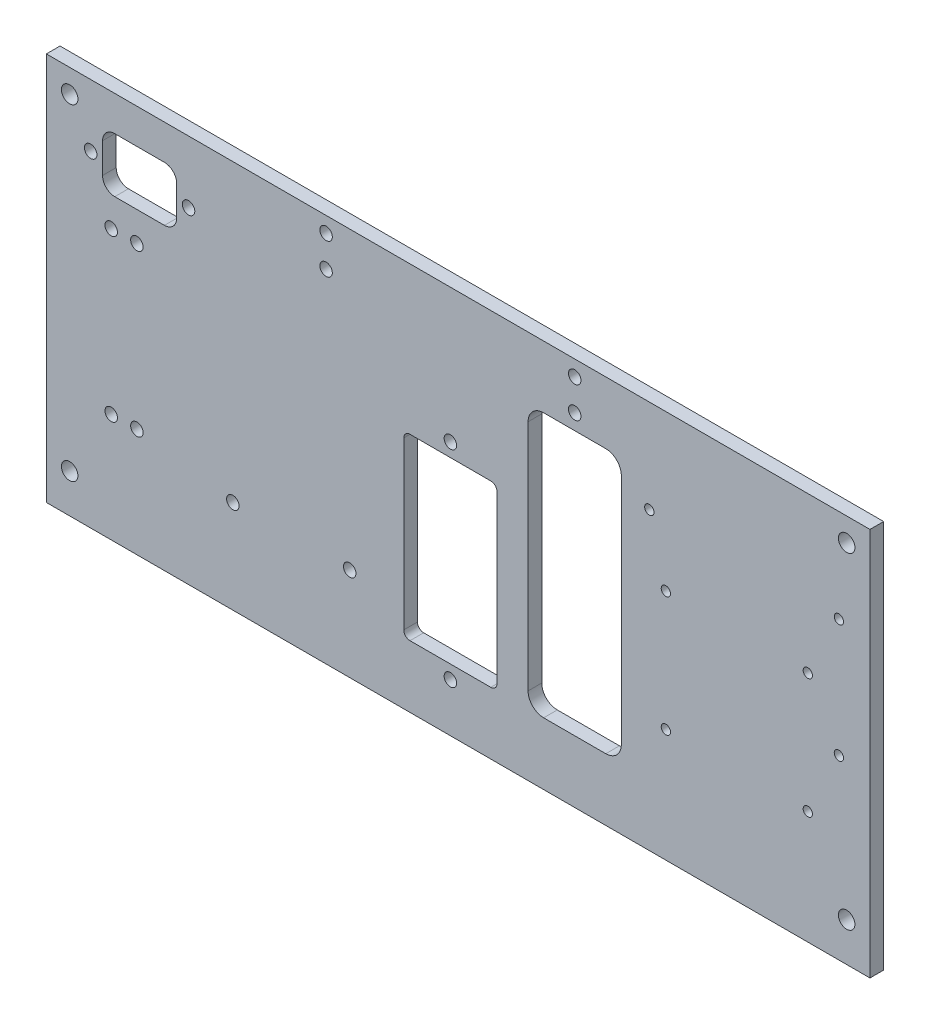
SolidWorks part; units mm, degrees
material "Acrylic (Medium-high impact)"
ref_plane "Front Plane" through (0, 0, 0) normal (0, 0, 1) x (1, 0, 0)
ref_plane "Top Plane" through (0, 0, 0) normal (0, 1, 0) x (1, 0, 0)
ref_plane "Right Plane" through (0, 0, 0) normal (1, 0, 0) x (0, 0, -1)
sketch "Sketch1" plane through (0, 0, 0) normal (0, 0, 1) x (1, 0, 0)
  line L1 (-168.275, 79.375) -> (168.275, 79.375)
  line L2 (-168.275, 79.375) -> (-168.275, -79.375)
  line L3 (-168.275, -79.375) -> (168.275, -79.375)
  line L4 (168.275, 79.375) -> (168.275, -79.375)
  line L5 (-168.275, 79.375) -> (168.275, -79.375) construction
  line L6 (-168.275, -79.375) -> (168.275, 79.375) construction
  point P0 (0, 0)
  dimension "D1" = 158.75
  dimension "D2" = 336.55
extrude "Boss-Extrude1" add sketch "Sketch1" along normal blind 5.588 contours L1 L4 L3 L2
hole_wizard "1/4 Clearance Hole1" positions "Sketch3" profile "Sketch2" hole size "1/4" standard "ANSI Inch" end condition up to next
sketch "Sketch3" plane through (0, 0, 0) normal (0, 0, -1) x (-1, 0, 0)
  line L1 (-158.75, 69.85) -> (158.75, 69.85) construction
  line L2 (-158.75, 69.85) -> (-158.75, -63.5) construction
  line L3 (-158.75, -63.5) -> (158.75, -63.5) construction
  line L4 (158.75, 69.85) -> (158.75, -63.5) construction
  line L5 (168.275, 79.375) -> (-168.275, 79.375) construction
  line L6 (-168.275, 79.375) -> (-168.275, -79.375) construction
  line L10 (168.275, 79.375) -> (168.275, -79.375) construction
  line L11 (168.275, -79.375) -> (-168.275, -79.375) construction
  point P1 (-158.75, 69.85)
  point P2 (158.75, -63.5)
  point P283 (-158.75, -63.5)
  point P284 (158.75, 69.85)
  dimension "D1" = 9.525
  dimension "D2" = 9.525
  dimension "D3" = 9.525
  dimension "D4" = 15.875
sketch "Sketch2" plane through (158.75, 69.85, 0) normal (1, 0, 0) x (0, 1, 0)
  line L0 (0, 0) -> (0, 5.588)
  line L1 (0, 5.588) -> (3.3782, 5.588)
  line L2 (3.3782, 5.588) -> (3.3782, 0)
  line L5 (3.3782, 0) -> (0, 0)
  line L11 (0, -6.35) -> (0, 107.95) construction
  dimension "Thru Hole Dia." = 6.7564
  dimension "Thru Hole Depth" = 5.588
hole_wizard "#6 Clearance Hole1" positions "Sketch6" profile "Sketch7" hole size "#6" standard "ANSI Inch" end condition up to next
sketch "Sketch6" plane through (0, 0, 0) normal (0, 0, -1) x (-1, 0, 0)
  line L1 (-155.575, 41.275) -> (-78.105, 41.275) construction
  line L2 (-155.575, 41.275) -> (-155.575, -6.985) construction
  line L3 (-155.575, -6.985) -> (-78.105, -6.985) construction
  line L4 (-78.105, 41.275) -> (-78.105, -6.985) construction
  line L5 (-168.275, 79.375) -> (-168.275, -79.375) construction
  line L6 (168.275, 79.375) -> (-168.275, 79.375) construction
  point P0 (-155.575, 41.275)
  point P105 (-155.575, -6.985)
  point P106 (-78.105, 41.275)
  dimension "D1" = 77.47
  dimension "D2" = 48.26
  dimension "D3" = 12.7
  dimension "D4" = 38.1
sketch "Sketch7" plane through (155.575, 41.275, 0) normal (1, 0, 0) x (0, 1, 0)
  line L0 (0, 0) -> (0, 5.588)
  line L1 (0, 5.588) -> (1.8986, 5.588)
  line L2 (1.8986, 5.588) -> (1.8986, 0)
  line L5 (1.8986, 0) -> (0, 0)
  line L11 (0, -6.35) -> (0, 107.95) construction
  dimension "Thru Hole Dia." = 3.7973
  dimension "Thru Hole Depth" = 5.588
hole_wizard "#6 Clearance Hole2" positions "Sketch9" profile "Sketch10" hole size "#6" standard "ANSI Inch" end condition up to next
sketch "Sketch9" plane through (0, 0, 0) normal (0, 0, -1) x (-1, 0, 0)
  line L1 (-142.875, 15.875) -> (-84.875, 15.875) construction
  line L2 (-142.875, 15.875) -> (-142.875, -33.125) construction
  line L3 (-142.875, -33.125) -> (-84.875, -33.125) construction
  line L4 (-84.875, 15.875) -> (-84.875, -33.125) construction
  line L5 (-168.275, 79.375) -> (-168.275, -79.375) construction
  line L6 (168.275, 79.375) -> (-168.275, 79.375) construction
  point P0 (-142.875, 15.875)
  point P1 (-84.875, -33.125)
  point P148 (-142.875, -33.125)
  point P149 (-84.875, 15.875)
  dimension "D1" = 58
  dimension "D2" = 49
  dimension "D3" = 25.4
  dimension "D4" = 63.5
sketch "Sketch10" plane through (142.875, 15.875, 0) normal (1, 0, 0) x (0, 1, 0)
  line L0 (0, 0) -> (0, 5.588)
  line L1 (0, 5.588) -> (1.8986, 5.588)
  line L2 (1.8986, 5.588) -> (1.8986, 0)
  line L5 (1.8986, 0) -> (0, 0)
  line L11 (0, -6.35) -> (0, 107.95) construction
  dimension "Thru Hole Dia." = 3.7973
  dimension "Thru Hole Depth" = 5.588
sketch "Sketch11" plane through (0, 0, 0) normal (0, 0, -1) x (-1, 0, 0)
  line L0 (168.275, 79.375) -> (168.275, -79.375) construction
  line L1 (-13.335, 19.05) -> (19.685, 19.05)
  line L2 (-15.875, 16.51) -> (-15.875, -51.435)
  line L3 (-13.335, -53.975) -> (19.685, -53.975)
  line L4 (22.225, 16.51) -> (22.225, -51.435)
  line L5 (168.275, -79.375) -> (-168.275, -79.375) construction
  arc A0 (19.685, 19.05) -> (22.225, 16.51) centre (19.685, 16.51) cw
  arc A1 (19.685, -53.975) -> (22.225, -51.435) centre (19.685, -51.435) ccw
  arc A2 (-15.875, -51.435) -> (-13.335, -53.975) centre (-13.335, -51.435) ccw
  arc A3 (-13.335, 19.05) -> (-15.875, 16.51) centre (-13.335, 16.51) ccw
  point P10 (22.225, 19.05)
  point P15 (-15.875, -53.975)
  point P18 (-15.875, 19.05)
  dimension "D5" = 2.54
  dimension "D1" = 38.1
  dimension "D2" = 73.025
  dimension "D3" = 146.05
  dimension "D4" = 25.4
extrude "Cut-Extrude1" cut sketch "Sketch11" against normal up to next
hole_wizard "#10 Clearance Hole1" positions "Sketch13" profile "Sketch14" hole size "#10" standard "ANSI Inch" end condition up to next
sketch "Sketch13" plane through (0, 0, 0) normal (0, 0, -1) x (-1, 0, 0)
  line L7 (-15.875, -17.4625) -> (3.175, -17.4625) construction
  line L8 (-15.875, 16.51) -> (-15.875, -51.435) construction
  line L10 (3.175, 24.6062) -> (3.175, -59.5313) construction
  point P12 (3.175, 24.6062)
  point P17 (3.175, -59.5313)
  dimension "D1" = 19.05
  dimension "D2" = 84.1375
sketch "Sketch14" plane through (-3.175, 24.6062, 0) normal (1, 0, 0) x (0, 1, 0)
  line L0 (0, 0) -> (0, 5.588)
  line L1 (0, 5.588) -> (2.5527, 5.588)
  line L2 (2.5527, 5.588) -> (2.5527, 0)
  line L5 (2.5527, 0) -> (0, 0)
  line L11 (0, -6.35) -> (0, 107.95) construction
  dimension "Thru Hole Dia." = 5.1054
  dimension "Thru Hole Depth" = 5.588
sketch "Sketch15" plane through (0, 0, 0) normal (0, 0, -1) x (-1, 0, 0)
  line L0 (-168.275, 79.375) -> (-168.275, -79.375) construction
  line L1 (-60.325, 53.975) -> (-34.925, 53.975)
  line L2 (-66.675, 47.625) -> (-66.675, -47.625)
  line L3 (-60.325, -53.975) -> (-34.925, -53.975)
  line L4 (-28.575, 47.625) -> (-28.575, -47.625)
  line L5 (168.275, 79.375) -> (-168.275, 79.375) construction
  line L6 (168.275, -79.375) -> (-168.275, -79.375) construction
  arc A0 (-34.925, 53.975) -> (-28.575, 47.625) centre (-34.925, 47.625) cw
  arc A1 (-34.925, -53.975) -> (-28.575, -47.625) centre (-34.925, -47.625) ccw
  arc A2 (-66.675, -47.625) -> (-60.325, -53.975) centre (-60.325, -47.625) ccw
  arc A3 (-60.325, 53.975) -> (-66.675, 47.625) centre (-60.325, 47.625) ccw
  point P12 (-28.575, 53.975)
  point P19 (-66.675, 53.975)
  dimension "D5" = 6.35
  dimension "D1" = 101.6
  dimension "D2" = 25.4
  dimension "D3" = 25.4
  dimension "D4" = 38.1
extrude "Cut-Extrude2" cut sketch "Sketch15" against normal up to next
hole_wizard "#10 Clearance Hole3" positions "Sketch17" profile "Sketch18" hole size "#10" standard "ANSI Inch" end condition up to next
sketch "Sketch17" plane through (0, 0, 0) normal (0, 0, -1) x (-1, 0, 0)
  line L4 (131.2799, 30.7848) -> (141.7701, 30.7848) construction
  line L7 (131.2799, -34.925) -> (141.7701, -34.925) construction
  line L9 (136.525, 30.7848) -> (136.525, -34.925) construction
  line L10 (168.275, 79.375) -> (168.275, -79.375) construction
  line L11 (168.275, -79.375) -> (-168.275, -79.375) construction
  point P0 (131.2799, 30.7848)
  point P1 (131.2799, -34.925)
  point P17 (141.7701, 30.7848)
  point P23 (141.7701, -34.925)
  dimension "D1" = 10.4902
  dimension "D2" = 65.7098
  dimension "D3" = 31.75
  dimension "D4" = 44.45
sketch "Sketch18" plane through (-131.2799, 30.7848, 0) normal (1, 0, 0) x (0, 1, 0)
  line L0 (0, 0) -> (0, 5.588)
  line L1 (0, 5.588) -> (2.5527, 5.588)
  line L2 (2.5527, 5.588) -> (2.5527, 0)
  line L5 (2.5527, 0) -> (0, 0)
  line L11 (0, -6.35) -> (0, 107.95) construction
  dimension "Thru Hole Dia." = 5.1054
  dimension "Thru Hole Depth" = 5.588
hole_wizard "#10 Clearance Hole2" positions "Sketch20" profile "Sketch21" hole size "#10" standard "ANSI Inch" end condition up to next
sketch "Sketch20" plane through (0, 0, 0) normal (0, 0, -1) x (-1, 0, 0)
  line L2 (-47.625, 73.025) -> (53.975, 73.025) construction
  line L3 (-47.625, 73.025) -> (-47.625, 60.325) construction
  line L4 (-47.625, 60.325) -> (53.975, 60.325) construction
  line L5 (53.975, 73.025) -> (53.975, 60.325) construction
  line L6 (168.275, 79.375) -> (168.275, -79.375) construction
  line L7 (168.275, 79.375) -> (-168.275, 79.375) construction
  point P3 (-47.625, 73.025)
  point P4 (53.975, 60.325)
  point P287 (-47.625, 60.325)
  point P288 (53.975, 73.025)
  dimension "D1" = 101.6
  dimension "D2" = 12.7
  dimension "D3" = 114.3
  dimension "D4" = 6.35
sketch "Sketch21" plane through (47.625, 73.025, 0) normal (1, 0, 0) x (0, 1, 0)
  line L0 (0, 0) -> (0, 5.588)
  line L1 (0, 5.588) -> (2.5527, 5.588)
  line L2 (2.5527, 5.588) -> (2.5527, 0)
  line L5 (2.5527, 0) -> (0, 0)
  line L11 (0, -6.35) -> (0, 107.95) construction
  dimension "Thru Hole Dia." = 5.1054
  dimension "Thru Hole Depth" = 5.588
hole_wizard "#10 Clearance Hole4" positions "Sketch23" profile "Sketch22" hole size "#10" standard "ANSI Inch" end condition up to next
sketch "Sketch23" plane through (0, 0, 0) normal (0, 0, -1) x (-1, 0, 0)
  line L0 (44.323, -41.275) -> (92.075, -41.275) construction
  line L6 (168.275, -79.375) -> (-168.275, -79.375) construction
  line L7 (168.275, 79.375) -> (168.275, -79.375) construction
  point P1 (44.323, -41.275)
  point P2 (92.075, -41.275)
  dimension "D1" = 47.752
  dimension "D2" = 38.1
  dimension "D3" = 76.2
sketch "Sketch22" plane through (-44.323, -41.275, 0) normal (1, 0, 0) x (0, 1, 0)
  line L0 (0, 0) -> (0, 5.588)
  line L1 (0, 5.588) -> (2.5527, 5.588)
  line L2 (2.5527, 5.588) -> (2.5527, 0)
  line L5 (2.5527, 0) -> (0, 0)
  line L11 (0, -6.35) -> (0, 107.95) construction
  dimension "Thru Hole Dia." = 5.1054
  dimension "Thru Hole Depth" = 5.588
sketch "Sketch24" plane through (0, 0, 0) normal (0, 0, -1) x (-1, 0, 0)
  line L0 (130.175, 65.125) -> (130.175, 42.825) construction
  line L1 (120.025, 65.125) -> (140.325, 65.125)
  line L2 (115.025, 60.125) -> (115.025, 47.825)
  line L3 (120.025, 42.825) -> (140.325, 42.825)
  line L4 (145.325, 60.125) -> (145.325, 47.825)
  line L5 (150.175, 53.975) -> (110.175, 53.975) construction
  line L6 (168.275, 79.375) -> (-168.275, 79.375) construction
  line L7 (168.275, 79.375) -> (168.275, -79.375) construction
  circle A0 centre (110.175, 53.975) radius 2.5527
  circle A1 centre (150.175, 53.975) radius 2.5527
  arc A2 (140.325, 65.125) -> (145.325, 60.125) centre (140.325, 60.125) cw
  arc A3 (140.325, 42.825) -> (145.325, 47.825) centre (140.325, 47.825) ccw
  arc A4 (115.025, 47.825) -> (120.025, 42.825) centre (120.025, 47.825) ccw
  arc A5 (120.025, 65.125) -> (115.025, 60.125) centre (120.025, 60.125) ccw
  point P9 (130.175, 53.975)
  point P13 (145.325, 65.125)
  point P16 (145.325, 42.825)
  point P21 (115.025, 65.125)
  dimension "D4" = 5.1054
  dimension "D5" = 5
  dimension "D1" = 30.3
  dimension "D2" = 22.3
  dimension "D3" = 40
  dimension "D6" = 25.4
  dimension "D7" = 38.1
extrude "Cut-Extrude3" cut sketch "Sketch24" against normal up to next
sketch "Sketch25" plane through (0, 0, 0) normal (0, 0, -1) x (-1, 0, 0)
  line L0 (-66.675, 47.625) -> (-66.675, -47.625) construction
  line L1 (-63.5, -22.225) -> (-89.535, -22.225)
  line L2 (-63.5, -22.225) -> (-63.5, 28.575)
  line L3 (-63.5, 28.575) -> (-89.535, 28.575)
  line L4 (-92.075, -19.685) -> (-92.075, 26.035)
  line L5 (168.275, 79.375) -> (-168.275, 79.375) construction
  arc A0 (-89.535, -22.225) -> (-92.075, -19.685) centre (-89.535, -19.685) cw
  arc A1 (-89.535, 28.575) -> (-92.075, 26.035) centre (-89.535, 26.035) ccw
  point P12 (-92.075, 28.575)
  dimension "D5" = 2.54
  dimension "D1" = 25.4
  dimension "D2" = 28.575
  dimension "D3" = 50.8
  dimension "D4" = 50.8
split line "Split Line1"
